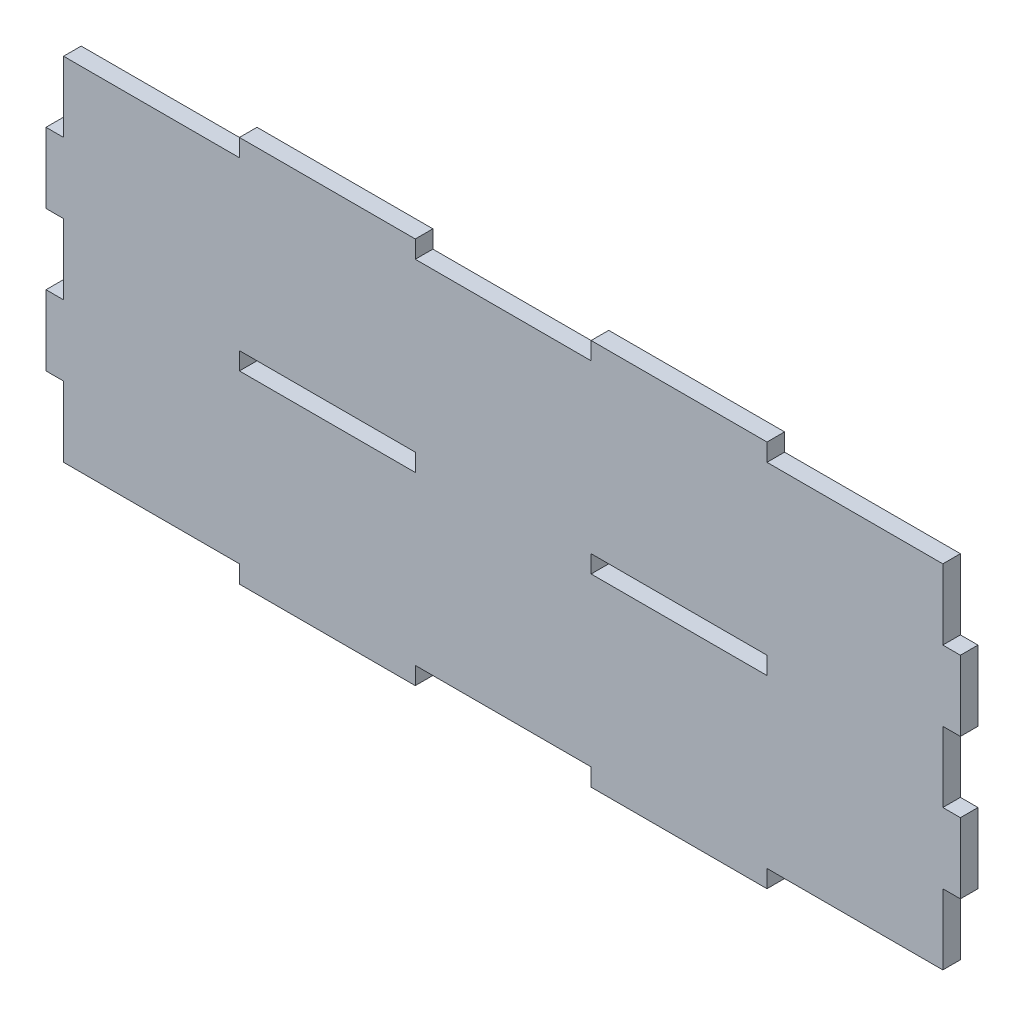
SolidWorks part; units mm, degrees
material "Pinho"
ref_plane "Plano frontal" through (0, 0, 0) normal (0, 0, 1) x (1, 0, 0)
ref_plane "Plano superior" through (0, 0, 0) normal (0, 1, 0) x (1, 0, 0)
ref_plane "Plano direito" through (0, 0, 0) normal (1, 0, 0) x (0, 0, -1)
sketch "Esboço1" plane through (0, 0, 0) normal (0, 0, 1) x (1, 0, 0)
  line L0 (45, 30) -> (75, 30)
  line L1 (-75, -30) -> (-45, -30)
  line L2 (-75, -30) -> (-75, -18)
  line L3 (-75, 30) -> (-45, 30)
  line L4 (75, -30) -> (75, -18)
  line L5 (-75, -30) -> (75, 30) construction
  line L6 (-75, 30) -> (75, -30) construction
  line L8 (-45, 30) -> (-45, 33)
  line L9 (-45, 33) -> (-15, 33)
  line L10 (-15, 30) -> (-15, 33)
  line L11 (-15, -30) -> (15, -30)
  line L12 (45, -30) -> (75, -30)
  line L14 (15, 30) -> (15, 33)
  line L15 (15, 33) -> (45, 33)
  line L16 (45, 30) -> (45, 33)
  line L17 (-15, 30) -> (15, 30)
  line L18 (-75, 18) -> (-75, 30)
  line L20 (-45, -30) -> (-45, -33)
  line L21 (-45, -33) -> (-15, -33)
  line L22 (-15, -30) -> (-15, -33)
  line L23 (-75, 18) -> (-78, 18)
  line L26 (15, -30) -> (15, -33)
  line L27 (15, -33) -> (45, -33)
  line L28 (45, -30) -> (45, -33)
  line L29 (-75, 6) -> (-78, 6)
  line L30 (-78, 18) -> (-78, 6)
  line L31 (-75, -6) -> (-75, 6)
  line L32 (75, -6) -> (75, 6)
  line L33 (-75, -18) -> (-78, -18)
  line L35 (-75, -6) -> (-78, -6)
  line L36 (-78, -18) -> (-78, -6)
  line L37 (75, 6) -> (78, 6)
  line L39 (75, 18) -> (78, 18)
  line L40 (78, 6) -> (78, 18)
  line L41 (75, 0) -> (-76.3343, 0) construction
  line L43 (75, -6) -> (78, -6)
  line L45 (75, -18) -> (78, -18)
  line L46 (78, -6) -> (78, -18)
  line L47 (75, 18) -> (75, 30)
  line L48 (45, 1.5) -> (15, 1.5)
  line L49 (45, 1.5) -> (45, -1.5)
  line L50 (45, -1.5) -> (15, -1.5)
  line L51 (15, 1.5) -> (15, -1.5)
  line L52 (45, 1.5) -> (15, -1.5) construction
  line L53 (45, -1.5) -> (15, 1.5) construction
  line L54 (-15, 1.5) -> (-45, 1.5)
  line L55 (-15, 1.5) -> (-15, -1.5)
  line L56 (-15, -1.5) -> (-45, -1.5)
  line L57 (-45, 1.5) -> (-45, -1.5)
  line L58 (-15, 1.5) -> (-45, -1.5) construction
  line L59 (-15, -1.5) -> (-45, 1.5) construction
  point P0 (0, 0)
  point P35 (30, 0)
  point P45 (-30, 0)
  dimension "D1" = 150
  dimension "D2" = 60
  dimension "D3" = 30
  dimension "D4" = 30
  dimension "D5" = 30
  dimension "D6" = 30
  dimension "D7" = 3
  dimension "D8" = 3
  dimension "D9" = 3
  dimension "D10" = 3
  dimension "D11" = 30
  dimension "D12" = 30
  dimension "D13" = 30
  dimension "D14" = 30
  dimension "D15" = 12
  dimension "D16" = 12
  dimension "D17" = 12
  dimension "D18" = 12
  dimension "D19" = 3
  dimension "D20" = 3
  dimension "D21" = 12
  dimension "D22" = 12
  dimension "D23" = 12
  dimension "D24" = 12
  dimension "D25" = 3
  dimension "D26" = 3
  dimension "D27" = 30
  dimension "D28" = 30
  dimension "D29" = 30
  dimension "D30" = 30
  dimension "D31" = 3
  dimension "D32" = 3
extrude "Ressalto-extrusão1" add sketch "Esboço1" along normal blind 3
